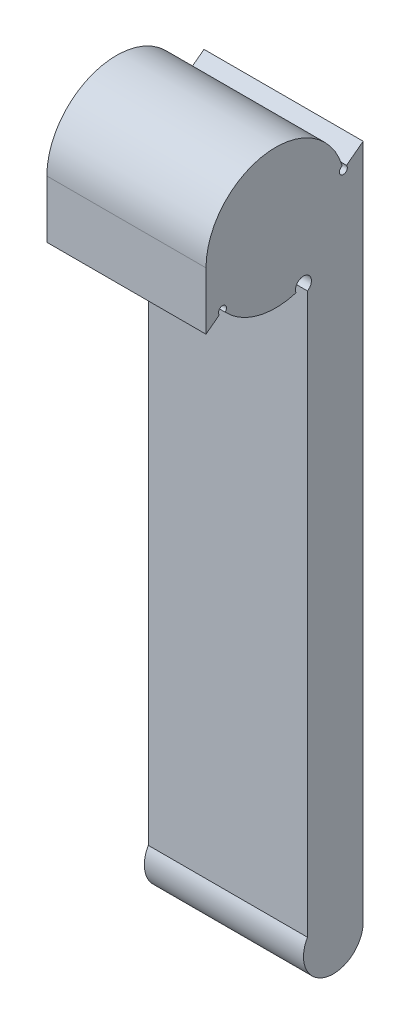
SolidWorks part; units mm, degrees
ref_plane "Front Plane" through (0, 0, 0) normal (1, 0, 0) x (0, 1, 0)
ref_plane "Top Plane" through (0, 0, 0) normal (0, 0, 1) x (0, 1, 0)
ref_plane "Right Plane" through (0, 0, 0) normal (0, 1, 0) x (-1, 0, 0)
sketch "Sketch1" plane through (0, 0, 0) normal (1, 0, 0) x (0, 1, 0)
  line L0 (24.6661, -15.2608) -> (21.7782, -15.2608)
  line L1 (21.7782, -15.2608) -> (22.4034, -16.0905)
  line L2 (22.4034, -16.0905) -> (24.6661, -15.2608)
  line L3 (24.6661, -18.7608) -> (21.1661, -18.7608) construction
  line L4 (25.4785, -22.1652) -> (26.2287, -23.1608)
  line L5 (26.2287, -23.1608) -> (-7.7713, -23.1608)
  line L7 (-7.7713, -20.1608) -> (21.4583, -20.1608)
  line L8 (25.4785, -22.1652) -> (21.4583, -20.1608)
  circle A0 centre (24.6661, -18.7608) radius 3.5
  circle A1 centre (24.6661, -18.7608) radius 0.2
  circle A2 centre (24.6661, -18.7608) radius 1.4
  arc A3 (-7.7713, -20.1608) -> (-7.7713, -23.1608) centre (-7.7713, -21.6608) ccw
  dimension "D1" = 7
  dimension "D2" = 0.4
  dimension "D3" = 2.8
  dimension "D4" = 53
  dimension "D5" = 3
  dimension "D6" = 34
extrude "Boss-Extrude1" add sketch "Sketch1" along normal blind 8
sketch "Sketch2" plane through (0, 0, 0) normal (-1, 0, 0) x (0, -1, 0)
  line L0 (-21.7782, -15.2608) -> (-22.4034, -16.0905) construction
  line L1 (-22.2546, -16.2241) -> (-22.2831, -15.9307)
  line L2 (-25.4785, -22.1652) -> (-26.2287, -23.1608) construction
  line L3 (-25.5989, -22.3249) -> (-25.6716, -22.1132)
  line L6 (7.7713, -20.1608) -> (-21.4583, -20.1608) construction
  line L7 (-21.1119, -20.3608) -> (7.0229, -20.3608)
  line L8 (-21.1119, -20.3608) -> (-21.4583, -20.1608)
  line L9 (-21.3195, -19.7856) -> (-21.3195, -20.1608)
  line L10 (-21.3195, -20.1608) -> (7.7713, -20.1608)
  arc A0 (-22.2831, -15.9307) -> (-22.2546, -16.2241) centre (-22.4034, -16.0905) ccw
  arc A1 (-21.4583, -20.1608) -> (-22.4034, -16.0905) centre (-24.6661, -18.7608) ccw construction
  arc A2 (-25.5989, -22.3249) -> (-25.6716, -22.1132) centre (-25.4785, -22.1652) ccw
  arc A3 (-24.6661, -15.2608) -> (-25.4785, -22.1652) centre (-24.6661, -18.7608) ccw construction
  arc A4 (-21.1119, -20.3608) -> (-21.3195, -19.7856) centre (-21.4583, -20.1608) cw
  arc A5 (7.7713, -20.1608) -> (7.0229, -20.3608) centre (7.7713, -21.6608) ccw
  arc A6 (7.7713, -23.1608) -> (7.7713, -20.1608) centre (7.7713, -21.6608) ccw construction
  line M11 (7.7713, -20.1608) -> (-21.4583, -20.1608)
  arc M12 (-21.4583, -20.1608) -> (-22.4034, -16.0905) centre (-24.6661, -18.7608) ccw
  line M13 (-22.4034, -16.0905) -> (-21.7782, -15.2608)
  arc M15 (-24.6661, -15.2608) -> (-25.4785, -22.1652) centre (-24.6661, -18.7608) ccw
  line M16 (-25.4785, -22.1652) -> (-26.2287, -23.1608)
  dimension "D1" = 0.2
  dimension "D2" = 0.2
  dimension "D3" = 0.4
  dimension "D4" = 0.2
extrude "Cut-Extrude1" cut sketch "Sketch2" against normal through all contours A0 M13 M12 | A4 L8 M12 | A2 M16 M15 | A5 L8 L7 M11 | L9 M12 M11 | L3 M16 M15 | L1 M12 M13
equation "\"D1@Sketch1\"=\"stand_pivot_diameter@clock_monsieur.Assembly\""
equation "\"D2@Sketch1\"=\"stand_pivot_inset@clock_monsieur.Assembly\"*2"
equation "\"D3@Sketch1\"=\"stand_pivot_inset@clock_monsieur.Assembly\"*2+\"back_thickness@clock_monsieur.Assembly\"*2"
equation "\"D6@Sketch1\"=\"stand_length@clock_monsieur.Assembly\""
equation "\"D1@Boss-Extrude1\"=\"stand_width@clock_monsieur.Assembly\""
equation "\"D4@Sketch1\"=\"stand_max_angle@clock_monsieur.Assembly\""
equation "\"D2@Sketch2\"=\"D1@Sketch2\""
equation "\"D3@Sketch2\"=\"D1@Sketch2\"*2"
equation "\"D4@Sketch2\"=\"D1@Sketch2\""
